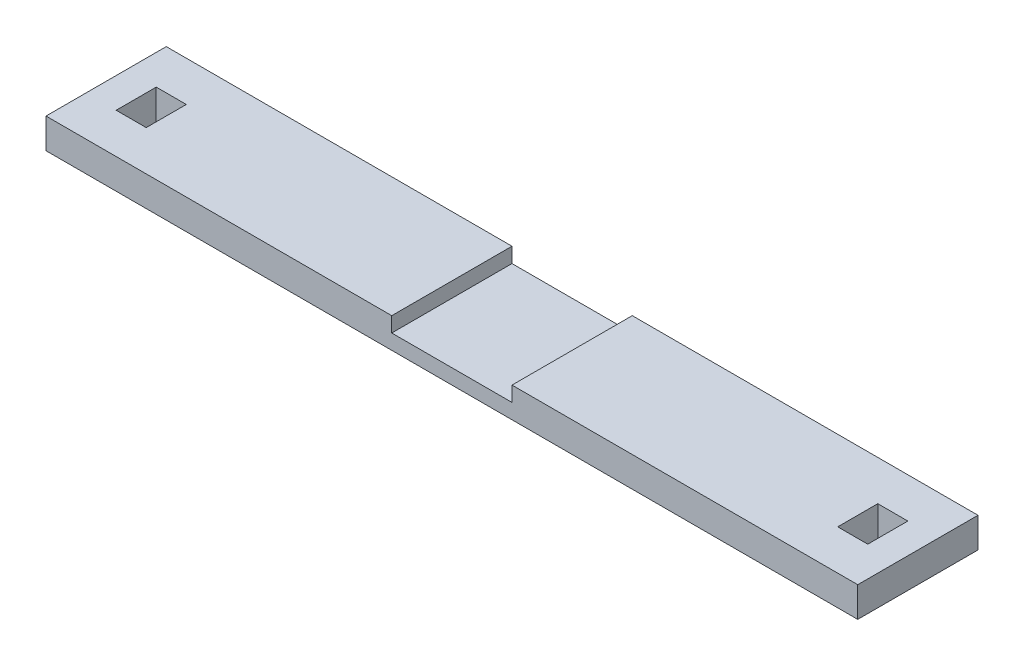
SolidWorks part; units mm, degrees
ref_plane "Front Plane" through (0, 0, 0) normal (0, 0, 1) x (1, 0, 0)
ref_plane "Top Plane" through (0, 0, 0) normal (0, 1, 0) x (1, 0, 0)
ref_plane "Right Plane" through (0, 0, 0) normal (1, 0, 0) x (0, 0, -1)
sketch "Sketch2" plane through (0, 0, 0) normal (0, 1, 0) x (1, 0, 0)
  line L1 (0, 0) -> (171.45, 0)
  line L2 (0, 0) -> (0, -25.4)
  line L3 (0, -25.4) -> (171.45, -25.4)
  line L4 (171.45, 0) -> (171.45, -25.4)
  dimension "D1" = 25.4
  dimension "D2" = 171.45
extrude "Boss-Extrude1" add sketch "Sketch2" along normal blind 6.35
sketch "Sketch3" plane through (0, 6.35, 0) normal (0, 1, 0) x (1, 0, 0)
  line L0 (171.45, -25.4) -> (171.45, 0) construction
  line L1 (158.75, -16.9333) -> (165.1, -16.9333)
  line L2 (158.75, -16.9333) -> (158.75, -8.4667)
  line L3 (158.75, -8.4667) -> (165.1, -8.4667)
  line L4 (165.1, -16.9333) -> (165.1, -8.4667)
  line L5 (171.45, 0) -> (0, 0) construction
  line L6 (0, 0) -> (0, -25.4) construction
  line L7 (6.35, -16.9333) -> (12.7, -16.9333)
  line L8 (6.35, -16.9333) -> (6.35, -8.4667)
  line L9 (6.35, -8.4667) -> (12.7, -8.4667)
  line L10 (12.7, -16.9333) -> (12.7, -8.4667)
  line L11 (0, -25.4) -> (171.45, -25.4) construction
  dimension "D1" = 8.4667
  dimension "D2" = 6.35
  dimension "D3" = 6.35
  dimension "D4" = 8.4667
  dimension "D5" = 8.4667
  dimension "D6" = 6.35
  dimension "D7" = 6.35
  dimension "D8" = 8.4667
extrude "Cut-Extrude1" cut sketch "Sketch3" against normal through all
sketch "Sketch4" plane through (0, 6.35, 0) normal (0, 1, 0) x (1, 0, 0)
  line L0 (171.45, 0) -> (0, 0) construction
  line L1 (73.025, 0) -> (98.425, 0)
  line L2 (73.025, 0) -> (73.025, -25.4)
  line L3 (73.025, -25.4) -> (98.425, -25.4)
  line L4 (98.425, 0) -> (98.425, -25.4)
  line L5 (0, -25.4) -> (171.45, -25.4) construction
  line L6 (171.45, -25.4) -> (171.45, 0) construction
  dimension "D1" = 25.4
  dimension "D2" = 73.025
extrude "Cut-Extrude2" cut sketch "Sketch4" against normal blind 3.175
